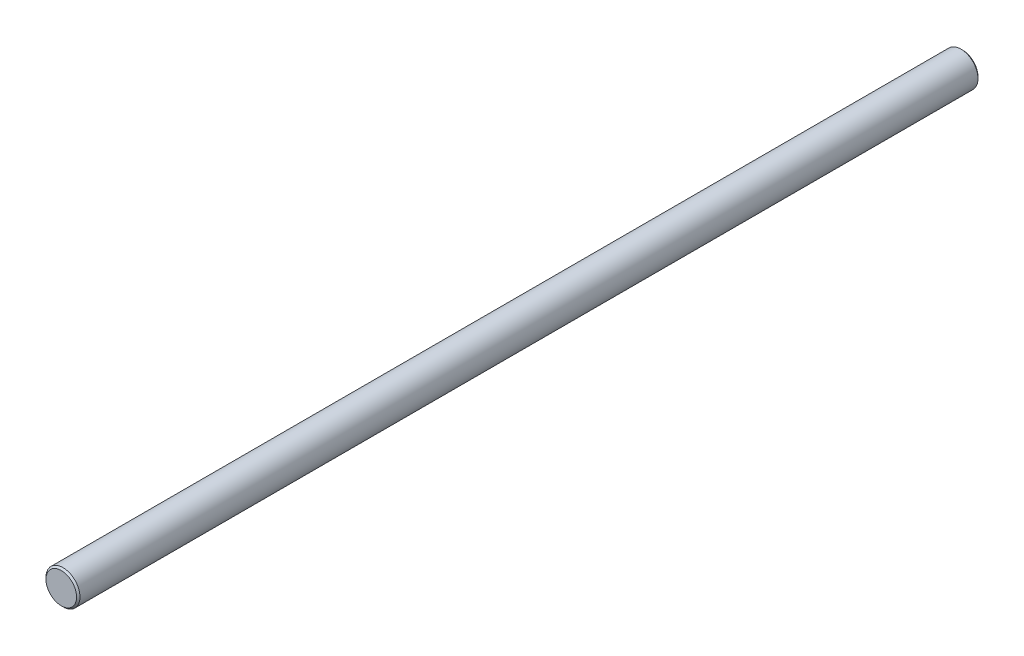
SolidWorks part; units mm, degrees
ref_plane "Front Plane" through (0, 0, 0) normal (0, 0, 1) x (1, 0, 0)
ref_plane "Top Plane" through (0, 0, 0) normal (0, 1, 0) x (1, 0, 0)
ref_plane "Right Plane" through (0, 0, 0) normal (1, 0, 0) x (0, 0, -1)
sketch "Sketch1" plane through (0, 0, 0) normal (0, 0, 1) x (1, 0, 0)
  circle A0 centre (0, 0) radius 1
  dimension "D1" = 2
extrude "Boss-Extrude1" add sketch "Sketch1" along normal blind 53
chamfer "Chamfer1" distance 0.1 angle 45 2 edges at (1, 0, 0) (1, 0, 53)
